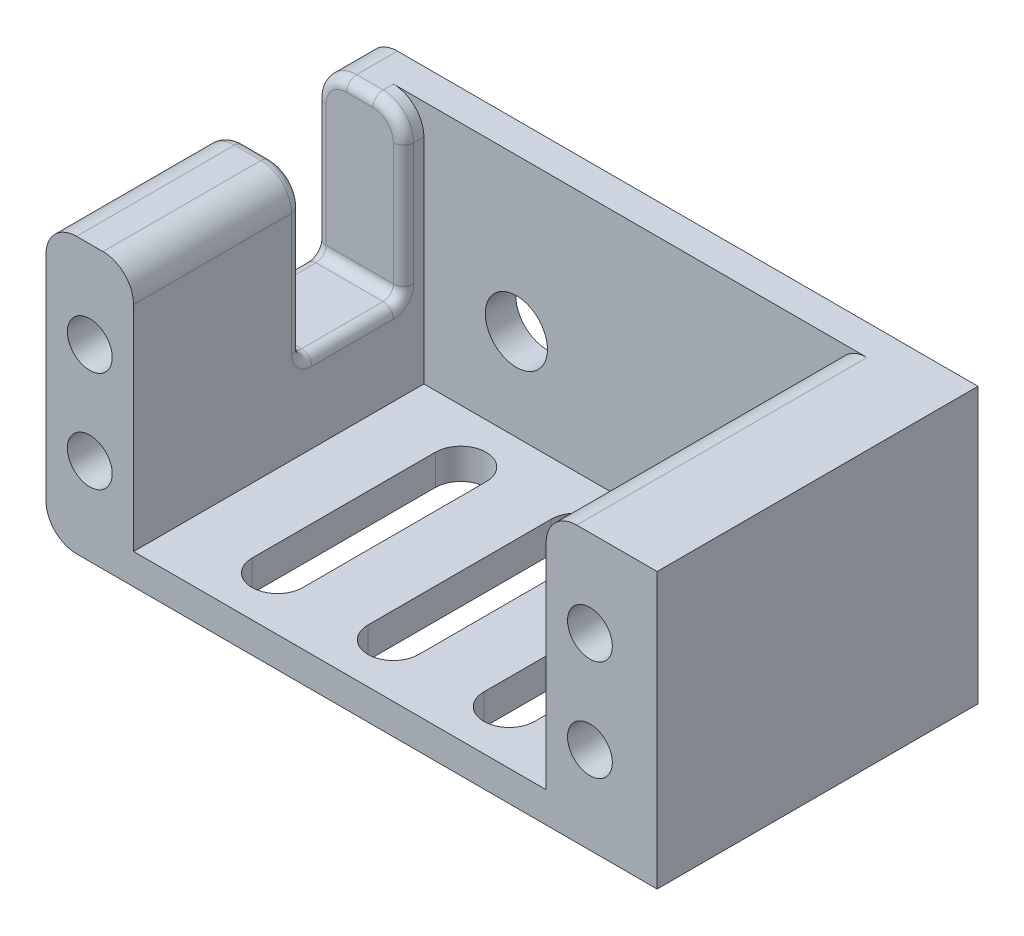
SolidWorks part; units mm, degrees
ref_plane "Front Plane" through (0, 0, 0) normal (0, 0, 1) x (1, 0, 0)
ref_plane "Top Plane" through (0, 0, 0) normal (0, 1, 0) x (1, 0, 0)
ref_plane "Right Plane" through (0, 0, 0) normal (1, 0, 0) x (0, 0, -1)
sketch "Sketch1" plane through (0, 0, 0) normal (0, 1, 0) x (1, 0, 0)
  line L0 (0, 0) -> (60, 0)
  line L6 (60, -31.5) -> (0, -31.5)
  line L7 (0, -31.5) -> (0, -26.5)
  line L9 (0, -26.5) -> (0, -3)
  line L11 (0, -3) -> (0, 0)
  line L12 (60, 0) -> (60, -31.5)
  dimension "D1" = 23.5
  dimension "D2" = 5
  dimension "D3" = 60
  dimension "D4" = 31.5
  dimension "D6" = 3
extrude "Boss-Extrude1" add sketch "Sketch1" along normal blind 27
sketch "Sketch2" plane through (0, 0, 31.5) normal (0, 0, 1) x (1, 0, 0)
  line L0 (0, 27) -> (0, 0) construction
  line L1 (0, 13.5) -> (60, 13.5) construction
  line L3 (60, 27) -> (60, 0) construction
  circle A0 centre (4.3, 18.45) radius 2.2
  circle A1 centre (4.3, 8.55) radius 2.2
  circle A2 centre (53.4, 18.45) radius 2.2
  circle A3 centre (53.4, 8.55) radius 2.2
  point P10 (28.85, 13.5)
  dimension "D1" = 4.3
  dimension "D2" = 4.4
  dimension "D3" = 9.9
  dimension "D4" = 4.95
  dimension "D8" = 4.4
  dimension "D9" = 9.9
  dimension "D10" = 49.1
  dimension "D11" = 4.95
  dimension "D12" = 4.4
extrude "Cut-Extrude1" cut sketch "Sketch2" against normal blind 5
sketch "Sketch4" plane through (0, 0, 31.5) normal (0, 0, 1) x (1, 0, 0)
  line L0 (49.1, 3) -> (8.6, 3)
  line L1 (49.1, 3) -> (49.1, 24)
  line L2 (49.1, 24) -> (8.6, 24)
  line L3 (8.6, 3) -> (8.6, 24)
  line L4 (0, 13.5) -> (60, 13.5) construction
  line L5 (0, 27) -> (0, 0) construction
  line L6 (60, 27) -> (60, 0) construction
  line L7 (8.6, 13.5) -> (49.1, 13.5) construction
  circle A0 centre (4.3, 18.45) radius 2.2 construction
  dimension "D1" = 4.3
  dimension "D2" = 40.5
  dimension "D3" = 21
extrude "Cut-Extrude2" cut sketch "Sketch4" against normal blind 28.5
sketch "Sketch5" plane through (0, 0, 31.5) normal (0, 0, 1) x (1, 0, 0)
  line L0 (8.6, 24) -> (8.6, 27)
  line L1 (8.6, 24) -> (49.1, 24)
  line L2 (8.6, 27) -> (49.1, 27)
  line L3 (49.1, 24) -> (49.1, 27)
  line L4 (0, 27) -> (60, 27) construction
  line L5 (49.1, 3) -> (49.1, 24) construction
  line L6 (49.1, 3) -> (49.1, 24) construction
extrude "Cut-Extrude4" cut sketch "Sketch5" against normal blind 28.5
sketch "Sketch10" plane through (0, 3, 0) normal (0, 1, 0) x (1, 0, 0)
  line L0 (28.85, -3) -> (28.85, -31.5) construction
  line L1 (49.1, -3) -> (8.6, -3) construction
  line L2 (8.6, -31.5) -> (49.1, -31.5) construction
  line L3 (8.6, -17.25) -> (49.1, -17.25) construction
  line L4 (8.6, -3) -> (8.6, -31.5) construction
  line L5 (49.1, -3) -> (49.1, -31.5) construction
  line L6 (28.85, -17.25) -> (26.35, -26.25) construction
  line L8 (31.35, -26.25) -> (31.35, -8.25)
  line L10 (26.35, -26.25) -> (26.35, -8.25)
  line L11 (28.85, -17.25) -> (26.35, -8.25) construction
  line L12 (31.35, -8.25) -> (28.85, -17.25) construction
  line L13 (31.35, -26.25) -> (28.85, -17.25) construction
  line L14 (42.73, -26.25) -> (42.73, -8.25)
  line L15 (37.73, -26.25) -> (37.73, -8.25)
  line L16 (40.23, -5.75) -> (40.23, -28.75) construction
  line L17 (19.97, -26.25) -> (19.97, -8.25)
  line L18 (14.97, -26.25) -> (14.97, -8.25)
  arc A0 (31.35, -8.25) -> (26.35, -8.25) centre (28.85, -8.25) ccw
  arc A1 (31.35, -26.25) -> (26.35, -26.25) centre (28.85, -26.25) cw
  arc A2 (42.73, -8.25) -> (37.73, -8.25) centre (40.23, -8.25) ccw
  arc A3 (42.73, -26.25) -> (37.73, -26.25) centre (40.23, -26.25) cw
  arc A4 (14.97, -26.25) -> (19.97, -26.25) centre (17.47, -26.25) ccw
  arc A5 (14.97, -8.25) -> (19.97, -8.25) centre (17.47, -8.25) cw
  point P12 (28.85, -17.25)
  point P20 (31.35, -17.25)
  point P22 (26.35, -17.25)
  dimension "D3" = 2.5
  dimension "D1" = 5
  dimension "D2" = 18
  dimension "D5" = 11.38
  dimension "D4" = 2
extrude "Cut-Extrude7" cut sketch "Sketch10" along direction (0, -1, 0) on the side against the normal up to surface (3 mm away)
sketch "Sketch6" plane through (8.6, 0, 0) normal (1, 0, 0) x (0, 0, -1)
  line L5 (-15, 27) -> (-5, 27)
  line L6 (-15, 27) -> (-15, 11)
  line L7 (-5, 27) -> (-5, 11)
  line L8 (-15, 11) -> (-5, 11)
  line L9 (-3, 27) -> (-31.5, 27) construction
  line L10 (-3, 27) -> (-3, 3) construction
  line L11 (-31.5, 15) -> (-3, 15) construction
  line L12 (-31.5, 27) -> (-31.5, 3) construction
  dimension "D3" = 2
  dimension "D4" = 10
  dimension "D5" = 4
extrude "Cut-Extrude5" cut sketch "Sketch6" against normal blind 28.5
fillet "Fillet1" radius 3 6 edges at (0, 0, 15.75) (0, 27, 2.5) (8.6, 27, 4) (0, 27, 23.25) (8.6, 27, 23.25) (49.1, 27, 17.25)
sketch "Sketch11" plane through (0, 0, 31.5) normal (0, 0, 1) x (1, 0, 0)
  line L0 (60, 13.5) -> (49.1, 13.5) construction
  line L1 (60, 27) -> (60, 0) construction
  line L2 (49.1, 3) -> (49.1, 24) construction
  line L3 (60, 24) -> (60, 3)
  line L4 (60, 24) -> (58.5, 24)
  line L5 (60, 3) -> (58.5, 3)
  line L6 (58.5, 24) -> (58.5, 3)
  line L7 (52.1, 27) -> (60, 27) construction
  point P6 (58.5, 13.5)
  dimension "D1" = 3
  dimension "D2" = 1.5
fillet "Fillet2" radius 1 14 edges at (4.3, 11, 5) (4.3, 11, 15) (4.3, 27, 15) (7.7213, 26.1213, 15) (0.8787, 26.1213, 15) (8.6, 17.5, 15) (0, 17.5, 15) (8.6, 11, 10) (0, 11, 10) (8.6, 17.5, 5) (7.7213, 26.1213, 5) (4.3, 27, 5) (0.8787, 26.1213, 5) (0, 17.5, 5)
sketch "Sketch9" plane through (0, 0, 0) normal (0, 0, -1) x (-1, 0, 0)
  line L0 (0, 12) -> (-58.987, 12) construction
  line L1 (0, 24) -> (0, 3) construction
  circle A0 centre (-17.68, 12) radius 3.05
  dimension "D1" = 17.68
  dimension "D2" = 6.1
extrude "Cut-Extrude6" cut sketch "Sketch9" against normal blind 10
